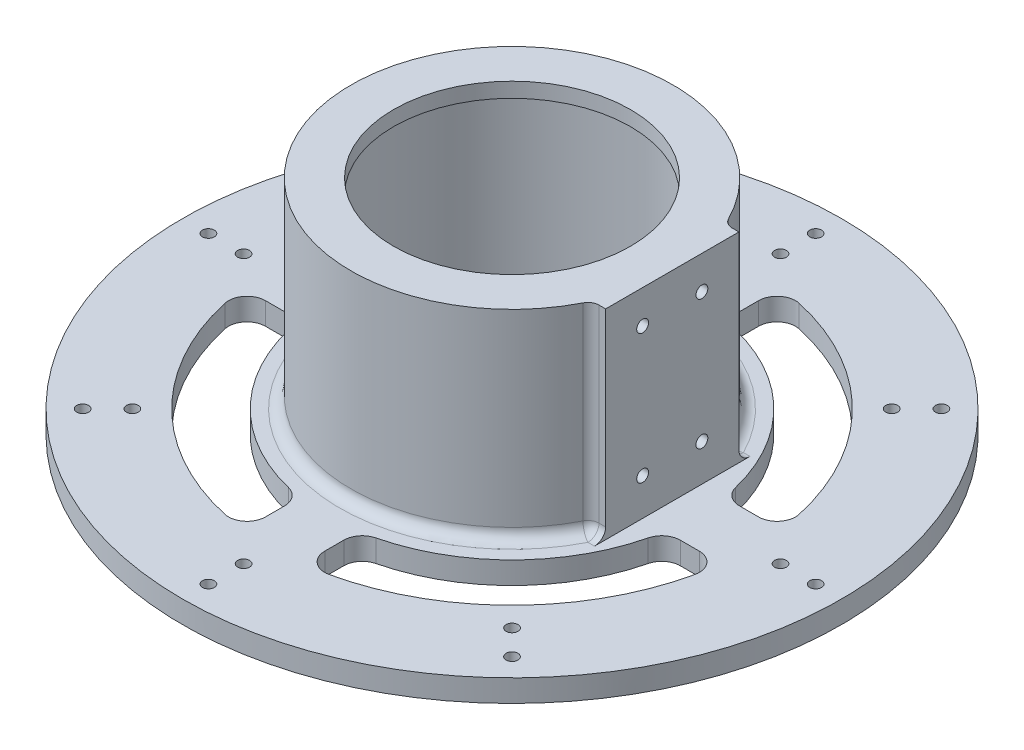
SolidWorks part; units mm, degrees
ref_plane "Front Plane" through (0, 0, 0) normal (0, 0, 1) x (1, 0, 0)
ref_plane "Top Plane" through (0, 0, 0) normal (0, 1, 0) x (1, 0, 0)
ref_plane "Right Plane" through (0, 0, 0) normal (1, 0, 0) x (0, 0, -1)
sketch "Sketch1" plane through (0, 0, 0) normal (0, 1, 0) x (1, 0, 0)
  line L0 (105.5, 0) -> (105.5, 60.5) construction
  line L1 (0, 0) -> (211, 0) construction
  line L2 (0, 0) -> (0, 121) construction
  line L3 (0, 121) -> (211, 121) construction
  line L4 (211, 0) -> (211, 121) construction
  line L5 (105.5, 60.5) -> (0, 60.5) construction
  circle A0 centre (105.5, 60.5) radius 75
  dimension "D3" = 150
  dimension "D1" = 211
  dimension "D2" = 121
extrude "Boss-Extrude1" add sketch "Sketch1" along normal blind 6
sketch "Sketch2" plane through (0, 0, 0) normal (0, -1, 0) x (1, 0, 0)
  circle A0 centre (105.5, -60.5) radius 70
  circle A1 centre (105.5, -60.5) radius 75 construction
  dimension "D1" = 5
extrude "Cut-Extrude1" [suppressed] cut sketch "Sketch2" against normal blind 7
sketch "Sketch3" plane through (0, 6, 0) normal (0, 1, 0) x (1, 0, 0)
  circle A0 centre (105.5, 60.5) radius 32
  circle A1 centre (105.5, 60.5) radius 75 construction
  dimension "D1" = 64
extrude "Cut-Extrude2" cut sketch "Sketch3" against normal through all
sketch "Sketch4" plane through (0, 6, 0) normal (0, 1, 0) x (1, 0, 0)
  line L0 (105.5, 60.5) -> (138.7754, 60.5) construction
  line L4 (138.7754, 75.5) -> (178.308, 75.5)
  line L5 (138.7754, 75.5) -> (138.7754, 45.5)
  line L6 (138.7754, 45.5) -> (178.308, 45.5)
  line L7 (178.308, 75.5) -> (178.308, 45.5)
  line L10 (145.7754, 75.5) -> (145.7754, 45.5)
  line L11 (148.7754, 78.5) -> (148.7754, 42.5)
  line L12 (145.1011, 78.5) -> (178.308, 78.5)
  line L14 (145.1011, 42.5) -> (178.308, 42.5)
  line L15 (178.308, 78.5) -> (178.308, 42.5)
  circle A0 centre (105.5, 60.5) radius 36.5 construction
  circle A1 centre (105.5, 60.5) radius 38.5
  circle A2 centre (105.5, 60.5) radius 75 construction
  circle A3 centre (105.5, 60.5) radius 32 construction
  arc A4 (148.7754, 64.9151) -> (148.7754, 56.0849) centre (105.5, 60.5) ccw
  dimension "D1" = 73
  dimension "D3" = 7
  dimension "D7" = 5
  dimension "D2" = 30
  dimension "D4" = 7
  dimension "D5" = 3
  dimension "D6" = 3
extrude "Boss-Extrude2" add sketch "Sketch4" along normal blind 50 contours A4 L6 A1 L4 | L6 A4 L11 L4 L10 | A4 L4 L11 L12 | A4 L11 L4 | A4 L6 L11 | A4 L14 L11 L6
sketch "Sketch5" plane through (148.7754, 0, 0) normal (1, 0, 0) x (0, 0, -1)
  line L0 (60.5, 56) -> (60.5, 51) construction
  line L1 (52.5, 51) -> (68.5, 51) construction
  line L2 (52.5, 51) -> (52.5, 16) construction
  line L3 (52.5, 16) -> (68.5, 16) construction
  line L4 (68.5, 51) -> (68.5, 16) construction
  line L9 (78.5, 56) -> (42.5, 56) construction
  circle A0 centre (52.5, 51) radius 1.6
  circle A1 centre (68.5, 51) radius 1.6
  circle A2 centre (68.5, 16) radius 1.6
  circle A3 centre (52.5, 16) radius 1.6
  dimension "D4" = 3.2
  dimension "D1" = 16
  dimension "D2" = 35
  dimension "D3" = 5
extrude "Cut-Extrude3" cut sketch "Sketch5" against normal blind 6
sketch "Sketch6" plane through (0, 6, 0) normal (0, 1, 0) x (1, 0, 0)
  circle A0 centre (105.5, 60.5) radius 75
  circle A1 centre (105.5, 60.5) radius 70
  circle A2 centre (105.5, 60.5) radius 75 construction
  dimension "D1" = 5
extrude "Boss-Extrude3" [suppressed] add sketch "Sketch6" along normal blind 10
sketch "Sketch7" plane through (0, 56, 0) normal (0, 1, 0) x (1, 0, 0)
  line L1 (145.1011, 78.5) -> (148.7754, 78.5)
  line L3 (145.1011, 42.5) -> (148.7754, 42.5)
  line L4 (148.7754, 78.5) -> (148.7754, 42.5)
  arc A0 (145.1011, 78.5) -> (145.1011, 42.5) centre (105.5, 60.5) ccw
  arc A3 (145.1011, 78.5) -> (145.1011, 42.5) centre (105.5, 60.5) ccw construction
  circle A4 centre (105.5, 60.5) radius 32
  circle A5 centre (105.5, 60.5) radius 32 construction
extrude "Boss-Extrude4" add sketch "Sketch7" along normal blind 4
sketch "Sketch8" plane through (0, 0, 0) normal (0, -1, 0) x (1, 0, 0)
  line L1 (140.9577, -45.5) -> (145.7754, -45.5)
  line L3 (140.9577, -75.5) -> (145.7754, -75.5)
  line L4 (145.7754, -45.5) -> (145.7754, -75.5)
  line L6 (145.7754, -75.5) -> (145.7754, -45.5) construction
  line L7 (140.9577, -45.5) -> (145.7754, -45.5) construction
  line L8 (140.9577, -75.5) -> (145.7754, -75.5) construction
  arc A0 (140.9577, -45.5) -> (140.9577, -75.5) centre (105.5, -60.5) ccw
  arc A1 (140.9577, -45.5) -> (140.9577, -75.5) centre (105.5, -60.5) ccw construction
extrude "Cut-Extrude4" cut sketch "Sketch8" against normal up to surface (6 mm away) up to face at (105.5, 6, -28.5)
sketch "Sketch9" [suppressed] plane through (0, 6, 0) normal (0, 1, 0) x (1, 0, 0)
  line L0 (160.2804, 20.2122) -> (43.2196, 87.7974)
  line L1 (98, 128.0851) -> (113, 128.0851)
  line L2 (98, 128.0851) -> (98, -7.0851)
  line L3 (98, -7.0851) -> (113, -7.0851)
  line L4 (113, 128.0851) -> (113, -7.0851)
  line L5 (167.7804, 33.2026) -> (50.7196, 100.7878)
  line L6 (43.2196, 33.2026) -> (160.2804, 100.7878)
  line L7 (50.7196, 20.2122) -> (167.7804, 87.7974)
  circle A0 centre (105.5, 60.5) radius 68
  circle A1 centre (105.5, 60.5) radius 51.5
  circle A2 centre (105.5, 60.5) radius 81 construction
  circle A3 centre (105.5, 60.5) radius 76 construction
  arc A4 (145.1011, 78.5) -> (145.1011, 42.5) centre (105.5, 60.5) ccw construction
  point P16 (105.5, 128.0851)
  point P26 (105.5, 60.5)
  dimension "D1" = 8
  dimension "D2" = 8
  dimension "D3" = 15
  dimension "D4" = 3
extrude "Cut-Extrude5" [suppressed] cut sketch "Sketch9" against normal up to surface (6 mm away) contours A1 L5 A0 L7 | A1 L4 A0 L0 | A1 L7 A0 L2 | A1 L0 A0 L6 | A1 L2 A0 L5 | A1 L6 A0 L4
fillet "Fillet1" radius 3 5 edges at (145.1011, 33, -78.5) (145.1011, 33, -42.5) (146.9383, 6, -78.5) (146.9383, 6, -42.5) (62, 6, -60.5)
fillet "Fillet2" [suppressed] radius 5
sketch "Sketch10" plane through (0, 0, 0) normal (0, -1, 0) x (1, 0, 0)
  circle A0 centre (105.5, -60.5) radius 75
  circle A1 centre (105.5, -60.5) radius 89
  circle A2 centre (105.5, -60.5) radius 82 construction
  circle A3 centre (105.5, -60.5) radius 75 construction
  circle A4 centre (105.5, 21.5) radius 1.6
  circle A5 centre (163.4828, -2.5172) radius 1.6
  circle A6 centre (187.5, -60.5) radius 1.6
  circle A7 centre (163.4828, -118.4828) radius 1.6
  circle A8 centre (105.5, -142.5) radius 1.6
  circle A9 centre (47.5172, -118.4828) radius 1.6
  circle A10 centre (23.5, -60.5) radius 1.6
  circle A11 centre (47.5172, -2.5172) radius 1.6
  point P9 (105.5, -60.5)
  point P10 (105.5, 20.5)
  point P26 (105.5, -60.5)
  dimension "D1" = 178
  dimension "D2" = 7
  dimension "D3" = 3.2
  dimension "D4" = 8
extrude "Boss-Extrude6" add sketch "Sketch10" against normal up to surface (6 mm away) up to face at (105.5, 6, 14.5)
sketch "Sketch11" plane through (0, 0, 0) normal (0, -1, 0) x (1, 0, 0)
  line L0 (97.5, -11.1441) -> (97.5, 4.0058)
  line L2 (97.5, -125.0058) -> (97.5, -109.8559)
  line L4 (113.5, -125.0058) -> (113.5, -109.8559)
  line L5 (40.9942, -68.5) -> (56.1441, -68.5)
  line L7 (40.9942, -52.5) -> (56.1441, -52.5)
  line L9 (154.8559, -68.5) -> (170.0058, -68.5)
  line L11 (113.5, -11.1441) -> (113.5, 4.0058)
  line L12 (154.8559, -52.5) -> (170.0058, -52.5)
  arc A0 (170.0058, -52.5) -> (113.5, 4.0058) centre (105.5, -60.5) ccw
  arc A1 (154.8559, -52.5) -> (113.5, -11.1441) centre (105.5, -60.5) ccw
  arc A2 (56.1441, -68.5) -> (97.5, -109.8559) centre (105.5, -60.5) ccw
  arc A3 (40.9942, -68.5) -> (97.5, -125.0058) centre (105.5, -60.5) ccw
  arc A4 (97.5, 4.0058) -> (40.9942, -52.5) centre (105.5, -60.5) ccw
  arc A5 (97.5, -11.1441) -> (56.1441, -52.5) centre (105.5, -60.5) ccw
  arc A6 (113.5, -109.8559) -> (154.8559, -68.5) centre (105.5, -60.5) ccw
  arc A7 (113.5, -125.0058) -> (170.0058, -68.5) centre (105.5, -60.5) ccw
  circle A8 centre (105.5, -60.5) radius 57.5 construction
  circle A9 centre (105.5, -118) radius 1.6
  circle A10 centre (48, -60.5) radius 1.6
  circle A11 centre (163, -60.5) radius 1.6
  circle A12 centre (105.5, -3) radius 1.6
  circle A13 centre (105.5, -60.5) radius 72.5 construction
  circle A14 centre (105.5, 12) radius 1.6
  circle A15 centre (156.7652, -9.2348) radius 1.6
  circle A16 centre (178, -60.5) radius 1.6
  circle A17 centre (156.7652, -111.7652) radius 1.6
  circle A18 centre (105.5, -133) radius 1.6
  circle A19 centre (54.2348, -111.7652) radius 1.6
  circle A20 centre (33, -60.5) radius 1.6
  circle A21 centre (54.2348, -9.2348) radius 1.6
  point P31 (105.5, -60.5)
  point P46 (105.5, -60.5)
  dimension "D1" = 130
  dimension "D2" = 15
  dimension "D7" = 7.5
  dimension "D8" = 3.2
  dimension "D9" = 145
  dimension "D10" = 3.2
  dimension "D3" = 8
  dimension "D4" = 16
  dimension "D5" = 8
  dimension "D6" = 16
  dimension "D11" = 8
extrude "Cut-Extrude6" cut sketch "Sketch11" against normal up to surface (6 mm away) contours A5 L0 A4 L7 | A1 L12 A0 L11 | L4 A7 L9 A6 | L5 A3 L2 A2 | A17 | A16 | A15 | A14 | A21 | A20 | A19 | A18 up to face at (125.8847, 6, -60.5)
fillet "Fillet3" radius 5 16 edges at (97.5, 3, -109.8559) (97.5, 3, -125.0058) (40.9942, 3, -68.5) (56.1441, 3, -52.5) (40.9942, 3, -52.5) (56.1441, 3, -68.5) (97.5, 3, 4.0058) (97.5, 3, -11.1441) (113.5, 3, 4.0058) (113.5, 3, -11.1441) (170.0058, 3, -52.5) (154.8559, 3, -52.5) (154.8559, 3, -68.5) (170.0058, 3, -68.5) (113.5, 3, -109.8559) (113.5, 3, -125.0058)
